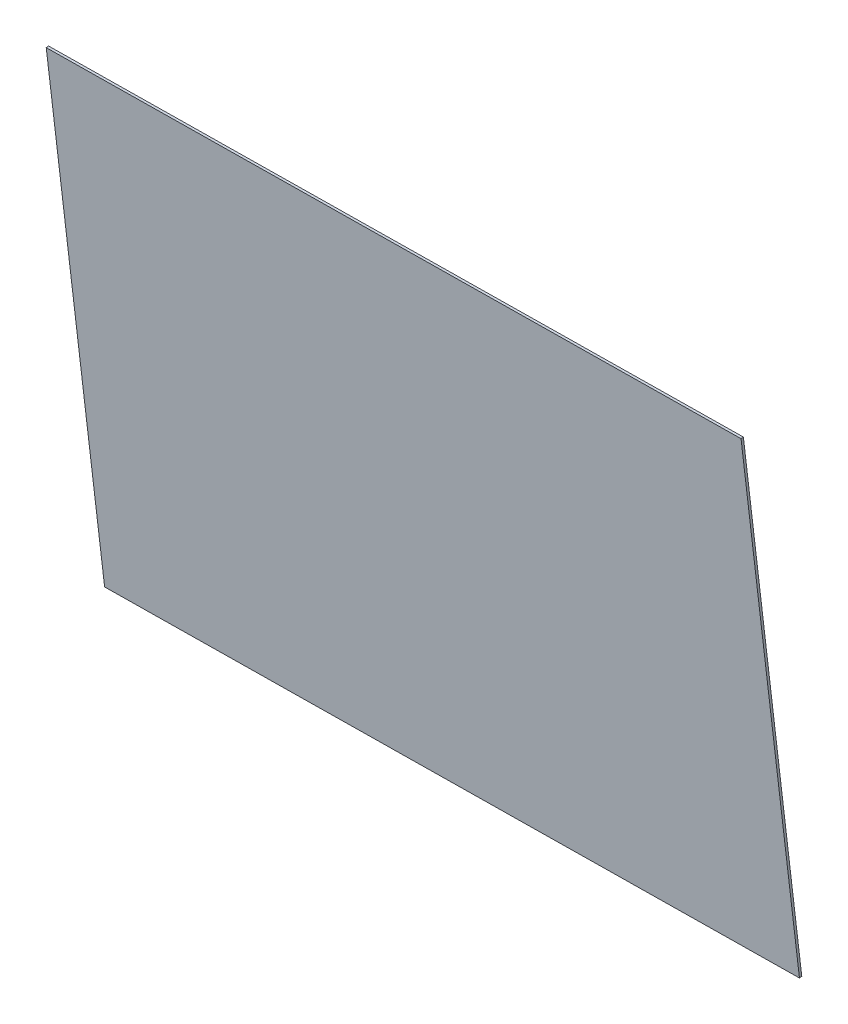
SolidWorks part; units mm, degrees
ref_plane "Front Plane" through (0, 0, 0) normal (0, 0, 1) x (1, 0, 0)
ref_plane "Top Plane" through (0, 0, 0) normal (0, 1, 0) x (1, 0, 0)
ref_plane "Right Plane" through (0, 0, 0) normal (1, 0, 0) x (0, 0, -1)
sketch "Sketch1" plane through (0, 21, -199.8015) normal (0, -0.1045, 0.9945) x (1, 0, 0)
  line L1 (131.0918, -701.9552) -> (428.062, -697.7455)
  line L2 (131.0918, -701.9552) -> (134.0683, -911.9341)
  line L3 (134.0683, -911.9341) -> (431.0385, -907.7244)
  line L4 (428.062, -697.7455) -> (431.0385, -907.7244)
  line L5 (131.0918, -701.9552) -> (431.0385, -907.7244) construction
  line L6 (134.0683, -911.9341) -> (428.062, -697.7455) construction
  point P4 (281.0651, -804.8398)
  point P7 (0, 0)
  point P8 (0, 0)
  point P9 (0, 0)
  point P10 (0, 0)
  point P11 (0, 0)
extrude "Boss-Extrude1" add sketch "Sketch1" along normal blind 1
